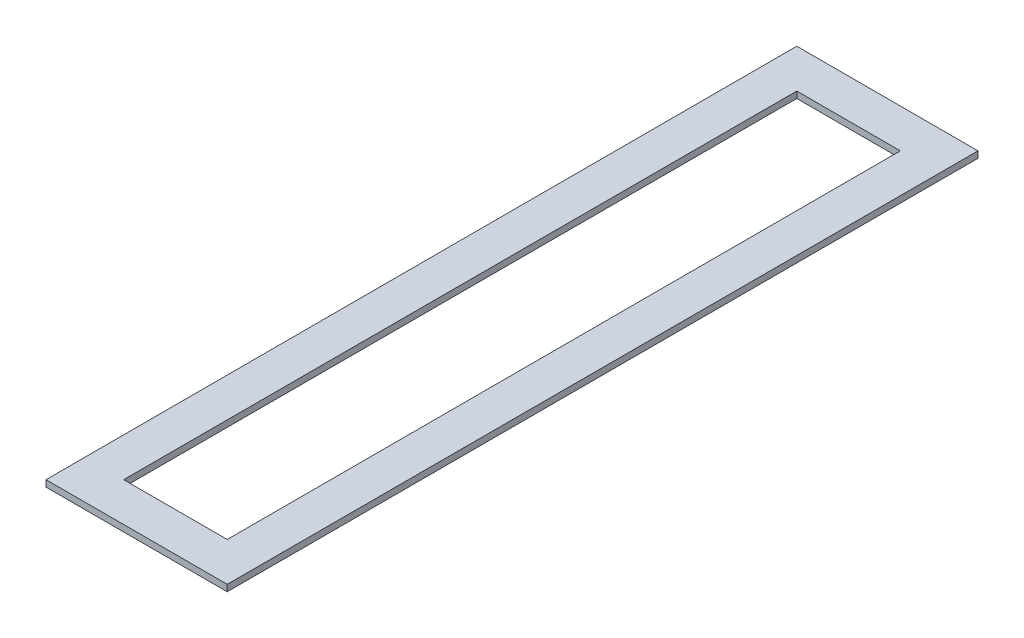
SolidWorks part; units mm, degrees
material "Copper"
ref_plane "Front Plane" through (0, 0, 0) normal (0, 0, 1) x (1, 0, 0)
ref_plane "Top Plane" through (0, 0, 0) normal (0, 1, 0) x (1, 0, 0)
ref_plane "Right Plane" through (0, 0, 0) normal (1, 0, 0) x (0, 0, -1)
sketch "Sketch6" plane through (0, 0, 0) normal (0, 1, 0) x (1, 0, 0)
  line L0 (-14, 58) -> (-14, -58)
  line L6 (-8, 52) -> (8, 52)
  line L7 (-14, -58) -> (14, -58)
  line L8 (14, 58) -> (14, -58)
  line L9 (-14, 58) -> (14, 58)
  line L10 (-8, 52) -> (-8, -52)
  line L11 (-8, -52) -> (8, -52)
  line L12 (8, 52) -> (8, -52)
  line L13 (-8, 52) -> (8, 52)
  line L14 (-8, 52) -> (-8, -52)
  line L15 (-8, -52) -> (8, -52)
  line L16 (8, 52) -> (8, -52)
  line L17 (-14, 58) -> (14, 58)
  line L18 (-14, 58) -> (-14, -58)
  line L19 (-14, -58) -> (14, -58)
  line L20 (14, 58) -> (14, -58)
  point P0 (0, 0)
extrude "Boss-Extrude1" add sketch "Sketch6" along normal blind 1 contours L9 L0 L7 L8 L6 L12 L11 L10
